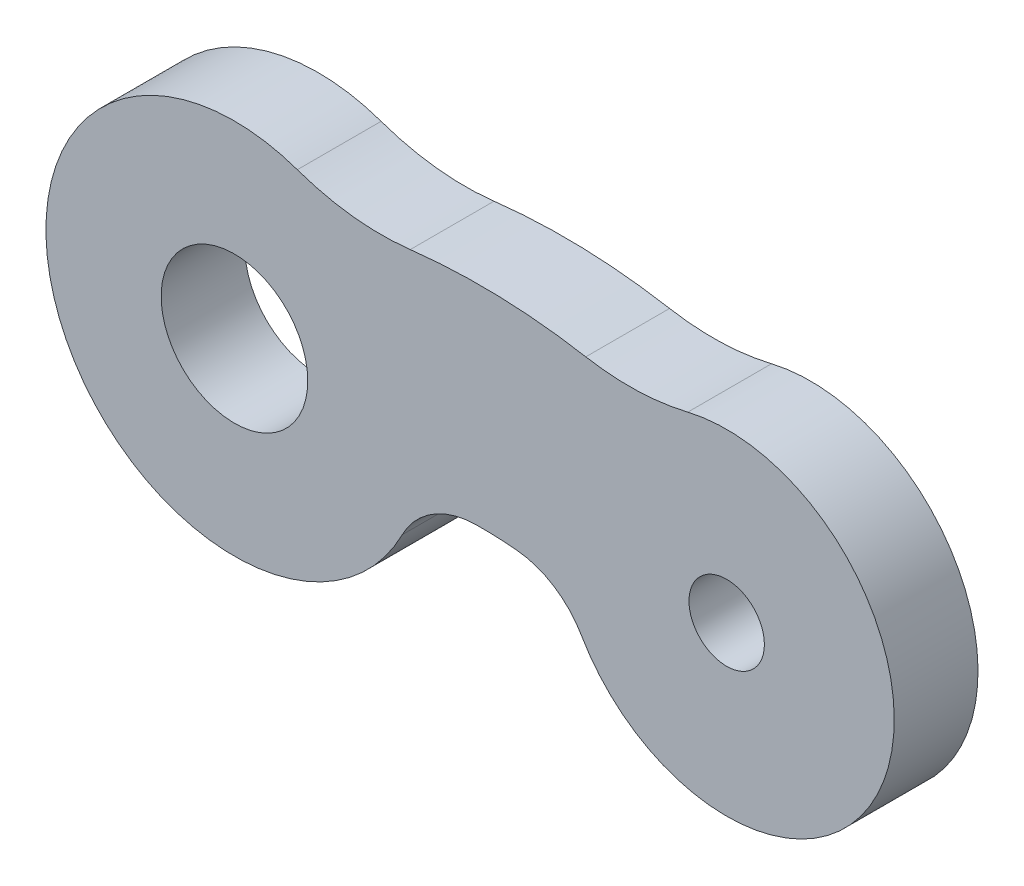
SolidWorks part; units mm, degrees
ref_plane "Front Plane" through (0, 0, 0) normal (0, 0, 1) x (1, 0, 0)
ref_plane "Top Plane" through (0, 0, 0) normal (0, 1, 0) x (1, 0, 0)
ref_plane "Right Plane" through (0, 0, 0) normal (1, 0, 0) x (0, 0, -1)
sketch "Sketch1" plane through (0, 0, 0) normal (0, 0, 1) x (1, 0, 0)
  line L0 (0, 0) -> (5.875, -10.4635) construction
  line L1 (11.75, 0) -> (5.875, -10.4635) construction
  line L2 (0, 0) -> (11.75, 0) construction
  circle A10 centre (0, 0) radius 1.75
  arc A11 (1.5009, 4.2423) -> (4.0049, -2.052) centre (0, 0) ccw
  circle A12 centre (11.75, 0) radius 0.9
  arc A13 (8.2836, -1.996) -> (10.8208, 3.8906) centre (11.75, 0) ccw
  arc A14 (4.1966, 3.9391) -> (8.3874, 3.8172) centre (5.875, -10.4635) cw
  arc A15 (5.7608, -0.9642) -> (6.7305, -1.0021) centre (5.875, -10.4635) cw
  arc A16 (0, 0) -> (12.0119, -0.1515) centre (5.875, -10.4635) cw construction
  arc A17 (8.3874, 3.8172) -> (10.8208, 3.8906) centre (9.427, 9.7264) ccw
  arc A18 (4.1966, 3.9391) -> (1.5009, 4.2423) centre (3.5022, 9.8987) cw
  arc A19 (6.7305, -1.0021) -> (8.2836, -1.996) centre (6.5504, -2.9939) cw
  arc A20 (5.7608, -0.9642) -> (4.0049, -2.052) centre (5.7849, -2.964) ccw
  dimension "D6" = 1.8
  dimension "D7" = 3.5
  dimension "D8" = 9
  dimension "D9" = 8
  dimension "D13" = 5
  dimension "D14" = 2.5
  dimension "D15" = 6
  dimension "D16" = 2
  dimension "D10" = 11.75
  dimension "D11" = 12
  dimension "D12" = 12
extrude "Boss-Extrude1" add sketch "Sketch1" along normal blind 2
